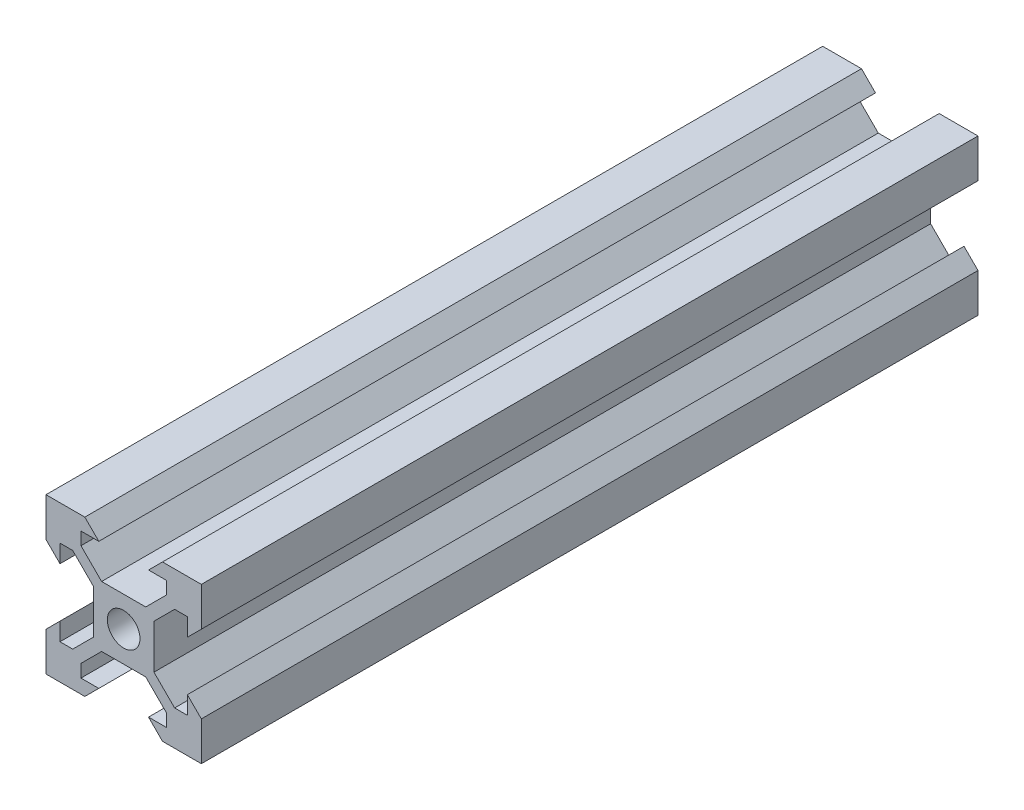
SolidWorks part; units mm, degrees
ref_plane "Front Plane" through (0, 0, 0) normal (0, 0, 1) x (1, 0, 0)
ref_plane "Top Plane" through (0, 0, 0) normal (0, 1, 0) x (1, 0, 0)
ref_plane "Right Plane" through (0, 0, 0) normal (1, 0, 0) x (0, 0, -1)
sketch "Sketch1" plane through (0, 0, 0) normal (0, 0, 1) x (1, 0, 0)
  line L0 (-10, 10) -> (-10, 5)
  line L1 (-10, 5) -> (-8.2, 3.2)
  line L2 (-8.2, 3.2) -> (-8.2, 5.4993)
  line L3 (-8.2, 5.4993) -> (-6.56, 5.4993)
  line L4 (-6.56, 5.4993) -> (-3.9007, 2.84)
  line L5 (-3.9007, 2.84) -> (-3.9007, -2.84)
  line L6 (-3.9007, -2.84) -> (-6.56, -5.4993)
  line L7 (-6.56, -5.4993) -> (-8.2, -5.4993)
  line L8 (-8.2, -5.4993) -> (-8.2, -3.2)
  line L9 (-8.2, -3.2) -> (-10, -5)
  line L10 (-10, -5) -> (-10, -10)
  line L11 (-10, -10) -> (-5, -10)
  line L12 (-5, -10) -> (-3.2, -8.2)
  line L13 (-3.2, -8.2) -> (-5.4993, -8.2)
  line L14 (-5.4993, -8.2) -> (-5.4993, -6.56)
  line L15 (-5.4993, -6.56) -> (-2.84, -3.9007)
  line L16 (-2.84, -3.9007) -> (2.84, -3.9007)
  line L17 (2.84, -3.9007) -> (5.4993, -6.56)
  line L18 (5.4993, -6.56) -> (5.4993, -8.2)
  line L19 (5.4993, -8.2) -> (3.2, -8.2)
  line L20 (3.2, -8.2) -> (5, -10)
  line L21 (5, -10) -> (10, -10)
  line L22 (10, -10) -> (10, -5)
  line L23 (10, -5) -> (8.2, -3.2)
  line L24 (8.2, -3.2) -> (8.2, -5.4993)
  line L25 (8.2, -5.4993) -> (6.56, -5.4993)
  line L26 (6.56, -5.4993) -> (3.9007, -2.84)
  line L27 (3.9007, -2.84) -> (3.9007, 2.84)
  line L28 (3.9007, 2.84) -> (6.56, 5.4993)
  line L29 (6.56, 5.4993) -> (8.2, 5.4993)
  line L30 (8.2, 5.4993) -> (8.2, 3.2)
  line L31 (8.2, 3.2) -> (10, 5)
  line L32 (10, 5) -> (10, 10)
  line L33 (10, 10) -> (5, 10)
  line L34 (5, 10) -> (3.2, 8.2)
  line L35 (3.2, 8.2) -> (5.4993, 8.2)
  line L36 (5.4993, 8.2) -> (5.4993, 6.56)
  line L37 (5.4993, 6.56) -> (2.84, 3.9007)
  line L38 (2.84, 3.9007) -> (-2.84, 3.9007)
  line L39 (-2.84, 3.9007) -> (-5.4993, 6.56)
  line L40 (-5.4993, 6.56) -> (-5.4993, 8.2)
  line L41 (-5.4993, 8.2) -> (-3.2, 8.2)
  line L42 (-3.2, 8.2) -> (-5, 10)
  line L43 (-5, 10) -> (-10, 10)
  circle A0 centre (0, 0) radius 2.1
extrude "Boss-Extrude1" add sketch "Sketch1" against normal blind 500
sketch "草图1" plane through (0, 0, 0) normal (0, 0, 1) x (1, 0, 0)
  line L1 (-13.9529, 12.8384) -> (13.9529, 12.8384)
  line L2 (-13.9529, 12.8384) -> (-13.9529, -12.8384)
  line L3 (-13.9529, -12.8384) -> (13.9529, -12.8384)
  line L4 (13.9529, 12.8384) -> (13.9529, -12.8384)
  line L5 (-13.9529, 12.8384) -> (13.9529, -12.8384) construction
  line L6 (-13.9529, -12.8384) -> (13.9529, 12.8384) construction
  point P0 (0, 0)
extrude "切除-拉伸1" cut sketch "草图1" against normal blind 400
sketch "草图3" plane through (0, 0, -500) normal (0, 0, -1) x (-1, 0, 0)
